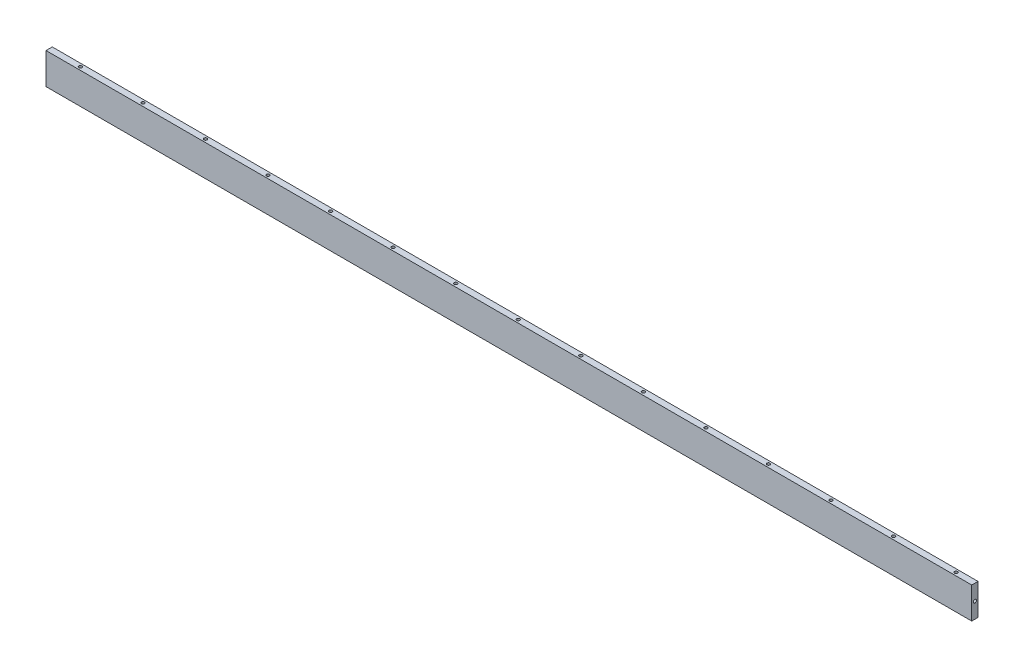
SolidWorks part; units mm, degrees
ref_plane "Alzado" through (0, 0, 0) normal (0, 0, 1) x (1, 0, 0)
ref_plane "Planta" through (0, 0, 0) normal (0, 1, 0) x (1, 0, 0)
ref_plane "Vista lateral" through (0, 0, 0) normal (1, 0, 0) x (0, 0, -1)
sketch "Croquis1" plane through (0, 0, 0) normal (0, 0, 1) x (1, 0, 0)
  line L1 (-740, -25) -> (740, -25)
  line L2 (-740, -25) -> (-740, 25)
  line L3 (-740, 25) -> (740, 25)
  line L4 (740, -25) -> (740, 25)
  line L5 (-740, -25) -> (740, 25) construction
  line L6 (-740, 25) -> (740, -25) construction
  point P0 (0, 0)
  dimension "D1" = 1480
  dimension "D2" = 50
extrude "Saliente-Extruir1" add sketch "Croquis1" along normal mid plane 10
sketch "Croquis2" plane through (0, 25, 0) normal (0, 1, 0) x (1, 0, 0)
  line L0 (-740, 0) -> (740, 0) construction
  line L1 (-740, -5) -> (-740, 5) construction
  line L2 (740, -5) -> (740, 5) construction
  circle A0 centre (-690, 0) radius 2.5
  circle A1 centre (-590, 0) radius 2.5
  circle A2 centre (-490, 0) radius 2.5
  circle A3 centre (-390, 0) radius 2.5
  circle A4 centre (-290, 0) radius 2.5
  circle A5 centre (-190, 0) radius 2.5
  circle A6 centre (-90, 0) radius 2.5
  circle A7 centre (10, 0) radius 2.5
  circle A8 centre (110, 0) radius 2.5
  circle A9 centre (210, 0) radius 2.5
  circle A10 centre (310, 0) radius 2.5
  circle A11 centre (410, 0) radius 2.5
  circle A12 centre (510, 0) radius 2.5
  circle A13 centre (610, 0) radius 2.5
  circle A14 centre (710, 0) radius 2.5
  dimension "D1" = 5
  dimension "D2" = 50
  dimension "D3" = 15
extrude "Cortar-Extruir1" cut sketch "Croquis2" against normal blind 5
sketch "Croquis3" plane through (740, 0, 0) normal (1, 0, 0) x (0, 0, -1)
  line L0 (0, 25) -> (0, -25) construction
  line L1 (-5, 25) -> (5, 25) construction
  line L2 (-5, -25) -> (5, -25) construction
  circle A0 centre (0, 0) radius 2.5
  dimension "D1" = 5
extrude "Cortar-Extruir2" cut sketch "Croquis3" against normal blind 5
mirror "Simetría1" about plane through (0, 0, 0) normal (1, 0, 0) of "Cortar-Extruir2"
